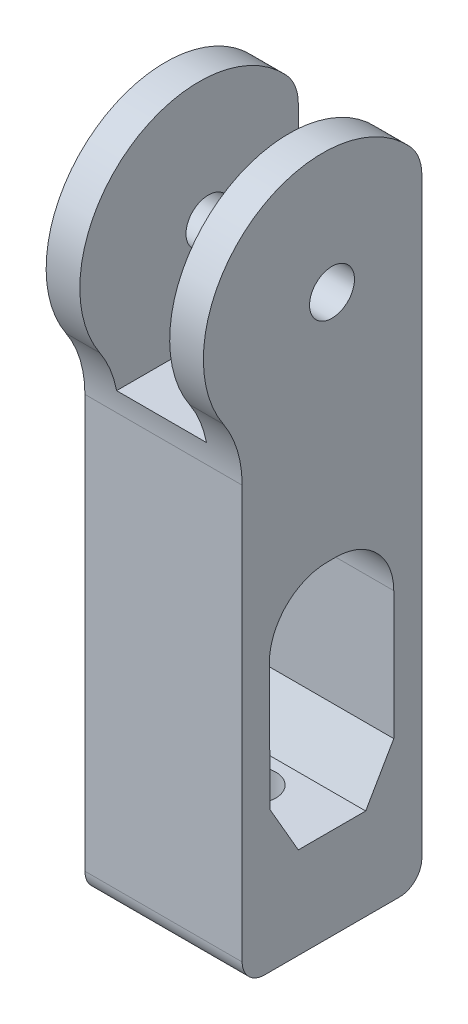
SolidWorks part; units mm, degrees
ref_plane "Piano frontale" through (0, 0, 0) normal (0, 0, 1) x (1, 0, 0)
ref_plane "Piano superiore" through (0, 0, 0) normal (0, 1, 0) x (1, 0, 0)
ref_plane "Piano destro" through (0, 0, 0) normal (1, 0, 0) x (0, 0, -1)
sketch "Sketch9" plane through (0, 0, 0) normal (1, 0, 0) x (0, 0, -1)
  line L0 (8, 5.0539) -> (8, -49.642)
  line L1 (8, -49.642) -> (-8, -49.642)
  line L2 (-8, -49.642) -> (-8, -10.8758)
  line L3 (5.5, -41.5) -> (5.5, -25.7624)
  line L5 (0.3362, -20.5986) -> (-0.4104, -20.5986)
  line L6 (-5.5741, -25.7867) -> (-5.5, -41.5)
  line L7 (-5.5, -41.5) -> (5.5, -41.5)
  line L8 (0, -49.642) -> (0, 21.1385) construction
  circle A0 centre (0, 0) radius 2
  arc A1 (6.9253, 7.782) -> (-9.6743, -5.3367) centre (-0.8371, 0.5427) ccw
  arc A2 (-8, -10.8758) -> (-9.6743, -5.3367) centre (-18, -10.8758) ccw
  arc A3 (8, 5.0539) -> (6.9253, 7.782) centre (4, 5.0539) ccw
  arc A4 (5.5, -25.7624) -> (0.3362, -20.5986) centre (0.3362, -25.7624) ccw
  arc A5 (-5.5741, -25.7867) -> (-0.4104, -20.5986) centre (-0.4104, -25.7624) cw
  point P24 (8, 6.4221)
  dimension "D1" = 4
  dimension "D2" = 10
  dimension "D3" = 4
  dimension "D4" = 5.1638
  dimension "D5" = 16
extrude "Boss-Extrude3" add sketch "Sketch9" along normal blind 14
sketch "Sketch10" plane through (0, -49.642, 0) normal (0, -1, 0) x (1, 0, 0)
  line L0 (7, 8) -> (7, -8) construction
  line L1 (14, 8) -> (0, 8) construction
  line L2 (14, -8) -> (0, -8) construction
  line L3 (0, 0) -> (18.4029, 0) construction
  line L5 (0, 8) -> (0, -8) construction
  circle A0 centre (7, 0) radius 2
  point P11 (7, 0)
  dimension "D1" = 4
extrude "Cut-Extrude7" cut sketch "Sketch10" against normal blind 14
ref_plane "Plane1" through (0, 16, 0) normal (0, 1, 0) x (1, 0, 0)
sketch "Sketch11" plane through (0, 16, 0) normal (0, 1, 0) x (1, 0, 0)
  line L0 (7, 8) -> (7, -11.4514) construction
  line L1 (14, 8) -> (0, 8) construction
  line L2 (0, -11.4514) -> (14, -11.4514) construction
  line L4 (11, -16.0587) -> (3, -16.0587)
  line L5 (11, -16.0587) -> (11, 10.6052)
  line L6 (11, 10.6052) -> (3, 10.6052)
  line L7 (3, -16.0587) -> (3, 10.6052)
  line L8 (11, -16.0587) -> (3, 10.6052) construction
  line L9 (11, 10.6052) -> (3, -16.0587) construction
  point P6 (7, -2.7267)
  dimension "D1" = 8
extrude "Cut-Extrude8" cut sketch "Sketch11" against normal blind 25
fillet "Fillet1" radius 2 2 edges at (7, -49.642, -8) (7, -49.642, 8)
chamfer "Chamfer1" distance 2.5 angle 60 2 edges at (7, -41.5, 5.5) (7, -41.5, -5.5)
